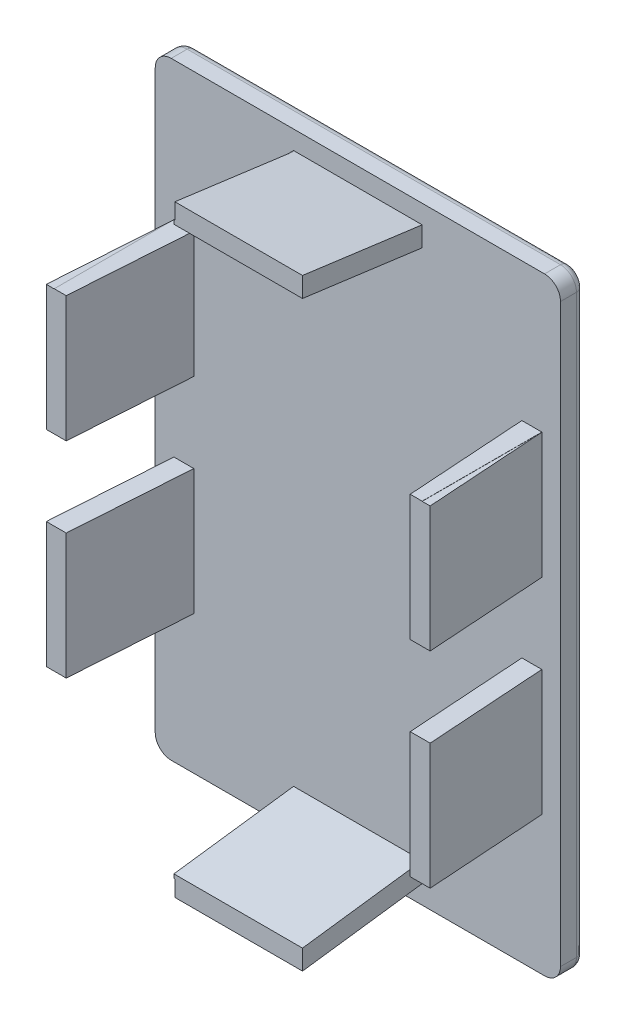
SolidWorks part; units mm, degrees
material "PLA"
ref_plane "Alzado" through (0, 0, 0) normal (0, 0, 1) x (1, 0, 0)
ref_plane "Planta" through (0, 0, 0) normal (0, 1, 0) x (1, 0, 0)
ref_plane "Vista lateral" through (0, 0, 0) normal (1, 0, 0) x (0, 0, -1)
sketch "Croquis1" plane through (0, 0, 0) normal (0, 0, 1) x (1, 0, 0)
  line L1 (25.4, 38.1) -> (-25.4, 38.1)
  line L2 (25.4, 38.1) -> (25.4, -38.1)
  line L3 (25.4, -38.1) -> (-25.4, -38.1)
  line L4 (-25.4, 38.1) -> (-25.4, -38.1)
  line L5 (25.4, 38.1) -> (-25.4, -38.1) construction
  line L6 (25.4, -38.1) -> (-25.4, 38.1) construction
  point P0 (0, 0)
  dimension "D1" = 76.2
  dimension "D2" = 50.8
extrude "Saliente-Extruir1" add sketch "Croquis1" along normal blind 18
sketch "Croquis2" plane through (0, 0, 18) normal (0, 0, 1) x (1, 0, 0)
  line L0 (25.4, 38.1) -> (-25.4, 38.1) construction
  line L1 (-23.06, 35.76) -> (23.06, 35.76)
  line L2 (-23.06, 35.76) -> (-23.06, -35.76)
  line L3 (-23.06, -35.76) -> (23.06, -35.76)
  line L4 (23.06, 35.76) -> (23.06, -35.76)
  line L5 (-25.4, -38.1) -> (25.4, -38.1) construction
  line L6 (-25.4, 38.1) -> (-25.4, -38.1) construction
  line L7 (25.4, -38.1) -> (25.4, 38.1) construction
  line L9 (-25.4, 38.1) -> (25.4, 38.1)
  line L10 (-25.4, 38.1) -> (-25.4, -38.1)
  line L11 (-25.4, -38.1) -> (25.4, -38.1)
  line L12 (25.4, 38.1) -> (25.4, -38.1)
  line L13 (-19.4, 32.1) -> (19.4, 32.1)
  line L14 (-19.4, 32.1) -> (-19.4, -32.1)
  line L15 (-19.4, -32.1) -> (19.4, -32.1)
  line L16 (19.4, 32.1) -> (19.4, -32.1)
  line M9 (-25.4, 38.1) -> (-25.4, -38.1)
  line M10 (-25.4, -38.1) -> (25.4, -38.1)
  line M11 (25.4, -38.1) -> (25.4, 38.1)
  line M12 (25.4, 38.1) -> (-25.4, 38.1)
  dimension "D1" = 2.34
  dimension "D2" = 2.34
  dimension "D3" = 2.34
  dimension "D4" = 2.34
  dimension "D5" = 6
  dimension "D6" = 6
  dimension "D7" = 6
  dimension "D8" = 6
extrude "Cortar-Extruir1" cut sketch "Croquis2" against normal blind 15 contours L1 L4 L3 L2 M12 M9 M10 M11 | L16 L13 L14 L15
sketch "Croquis3" plane through (0, 0, 18) normal (0, 0, 1) x (1, 0, 0)
  line L0 (-23.06, 35.76) -> (-23.06, -35.76) construction
  line L1 (-23.06, 22.1) -> (-19.4, 22.1)
  line L2 (-23.06, 22.1) -> (-23.06, -22.1)
  line L3 (-23.06, -22.1) -> (-19.4, -22.1)
  line L4 (-19.4, 22.1) -> (-19.4, -22.1)
  line L5 (-19.4, 32.1) -> (-19.4, -32.1) construction
  line L6 (-19.4, -32.1) -> (19.4, -32.1) construction
  line L7 (-9.4, -32.1) -> (9.3837, -32.1)
  line L8 (-9.4, -32.1) -> (-9.4, -35.76)
  line L9 (-9.4, -35.76) -> (9.3837, -35.76)
  line L10 (9.3837, -32.1) -> (9.3837, -35.76)
  line L11 (-23.06, -35.76) -> (23.06, -35.76) construction
  line L12 (19.4, 32.1) -> (19.4, -32.1) construction
  line L13 (19.4, -22.1) -> (23.06, -22.1)
  line L14 (19.4, -22.1) -> (19.4, 22.1)
  line L15 (19.4, 22.1) -> (23.06, 22.1)
  line L16 (23.06, -22.1) -> (23.06, 22.1)
  line L17 (23.06, 35.76) -> (23.06, -35.76) construction
  line L18 (-23.06, 35.76) -> (23.06, 35.76) construction
  line L19 (-9.4, 35.76) -> (9.4, 35.76)
  line L20 (-9.4, 35.76) -> (-9.4, 32.1)
  line L21 (-9.4, 32.1) -> (9.4, 32.1)
  line L22 (9.4, 35.76) -> (9.4, 32.1)
  line L23 (-19.4, 32.1) -> (19.4, 32.1) construction
  line L24 (-19.4, 32.1) -> (-19.4, -32.1) construction
  line L25 (19.4, 32.1) -> (19.4, -32.1) construction
  dimension "D1" = 10
  dimension "D2" = 10
  dimension "D3" = 10
  dimension "D4" = 10
  dimension "D5" = 10
  dimension "D6" = 10
  dimension "D7" = 10
extrude "Cortar-Extruir2" [suppressed] cut sketch "Croquis3" against normal blind 7
fillet "Redondeo1" [suppressed] radius 2
fillet "Redondeo2" [suppressed] radius 1
sketch "Croquis5" [suppressed] plane through (0, -38.1, 0) normal (0, -1, 0) x (1, 0, 0)
  line L0 (-23.4, 3) -> (23.4, 3) construction
  line L1 (-3, 3) -> (3, 3)
  line L2 (-3, 3) -> (-3, 1.5)
  line L3 (-3, 1.5) -> (3, 1.5)
  line L4 (3, 3) -> (3, 1.5)
  line L5 (0, 1) -> (0, 3) construction
  line L6 (-23.4, 1) -> (23.4, 1) construction
  dimension "D1" = 3
  dimension "D2" = 3
  dimension "D3" = 1.5
extrude "Cortar-Extruir4" [suppressed] cut sketch "Croquis5" against normal blind 6
sketch "Croquis6" plane through (0, 0, 18) normal (0, 0, 1) x (1, 0, 0)
  line L0 (-23.06, 35.76) -> (-8.06, 35.76)
  line L1 (-23.06, 35.76) -> (23.06, 35.76) construction
  line L2 (-8.06, 35.76) -> (-8.06, 32.1)
  line L3 (-19.4, 32.1) -> (19.4, 32.1) construction
  line L4 (-8.06, 32.1) -> (-19.4, 32.1)
  line L5 (-19.4, 32.1) -> (-19.4, 20.76)
  line L6 (-19.4, 32.1) -> (-19.4, -32.1) construction
  line L7 (-19.4, 20.76) -> (-23.06, 20.76)
  line L8 (-23.06, 35.76) -> (-23.06, -35.76) construction
  line L9 (-23.06, 20.76) -> (-23.06, 35.76)
  line L10 (23.06, 35.76) -> (8.06, 35.76)
  line L11 (-23.06, 35.76) -> (23.06, 35.76) construction
  line L12 (8.06, 35.76) -> (8.06, 32.1)
  line L13 (8.06, 32.1) -> (19.4, 32.1)
  line L14 (19.4, 32.1) -> (19.4, -32.1) construction
  line L15 (19.4, 32.1) -> (19.4, -32.1) construction
  line L16 (19.4, 32.1) -> (19.4, 20.76)
  line L17 (19.4, 20.76) -> (23.06, 20.76)
  line L18 (23.06, 35.76) -> (23.06, -35.76) construction
  line L19 (23.06, 20.76) -> (23.06, 35.76)
  line L20 (-23.06, -35.76) -> (-23.06, -20.76)
  line L21 (-23.06, 35.76) -> (-23.06, -35.76) construction
  line L22 (-23.06, -20.76) -> (-19.4, -20.76)
  line L23 (-19.4, 32.1) -> (-19.4, -32.1) construction
  line L24 (-19.4, -20.76) -> (-19.4, -32.1)
  line L25 (-19.4, -32.1) -> (-8.06, -32.1)
  line L26 (-19.4, -32.1) -> (19.4, -32.1) construction
  line L27 (-8.06, -32.1) -> (-8.06, -35.76)
  line L28 (-23.06, -35.76) -> (23.06, -35.76) construction
  line L29 (-8.06, -35.76) -> (-23.06, -35.76)
  line L30 (23.06, -35.76) -> (8.06, -35.76)
  line L31 (-23.06, -35.76) -> (23.06, -35.76) construction
  line L32 (8.06, -35.76) -> (8.06, -32.1)
  line L33 (-19.4, -32.1) -> (19.4, -32.1) construction
  line L34 (8.06, -32.1) -> (19.4, -32.1)
  line L35 (19.4, -32.1) -> (19.4, -20.76)
  line L36 (19.4, -20.76) -> (23.06, -20.76)
  line L37 (23.06, 35.76) -> (23.06, -35.76) construction
  line L38 (23.06, -20.76) -> (23.06, -35.76)
  dimension "D1" = 15
  dimension "D2" = 15
  dimension "D3" = 15
  dimension "D4" = 15
  dimension "D5" = 15
  dimension "D6" = 15
  dimension "D7" = 15
  dimension "D8" = 15
extrude "Cortar-Extruir8" cut sketch "Croquis6" against normal blind 15
sketch "Croquis10" plane through (0, -20.76, 0) normal (0, -1, 0) x (-1, 0, 0)
  line L0 (23.06, -18) -> (24.06, -18)
  line L1 (24.06, -18) -> (23.06, -3)
  line L2 (23.06, -3) -> (23.06, -18)
  line L3 (-23.06, -18) -> (-24.06, -18)
  line L4 (-24.06, -18) -> (-23.06, -3)
  line L5 (-23.06, -3) -> (-23.06, -18)
  dimension "D1" = 1
  dimension "D2" = 1
extrude "Saliente-Extruir3" add sketch "Croquis10" against normal blind 41.5
sketch "Croquis11" plane through (0, -20.76, 0) normal (0, -1, 0) x (1, 0, 0)
  line L0 (-19.4, 18) -> (-21.56, 18)
  line L1 (-19.4, 18) -> (-24.06, 18) construction
  line L2 (-21.56, 18) -> (-20.56, 3)
  line L3 (-19.4, 3) -> (-23.06, 3) construction
  line L4 (-20.56, 3) -> (-19.4, 3)
  line L5 (-19.4, 18) -> (-19.4, 3)
  dimension "D1" = 2.5
  dimension "D2" = 1.16
extrude "Cortar-Extruir9" cut sketch "Croquis11" against normal blind 51.5
sketch "Croquis12" plane through (0, -20.76, 0) normal (0, -1, 0) x (1, 0, 0)
  line L0 (19.4, 18) -> (19.4, 3)
  line L1 (19.4, 3) -> (20.56, 3)
  line L2 (23.06, 3) -> (19.4, 3) construction
  line L3 (20.56, 3) -> (21.56, 18)
  line L4 (24.06, 18) -> (19.4, 18) construction
  line L5 (21.56, 18) -> (19.4, 18)
  dimension "D1" = 2.5
  dimension "D2" = 1.16
extrude "Cortar-Extruir10" cut sketch "Croquis12" against normal blind 51.5
sketch "Croquis13" plane through (8.06, 0, 0) normal (1, 0, 0) x (0, 0, -1)
  line L0 (-18, -35.76) -> (-18, -37.76)
  line L1 (-18, -37.76) -> (-3, -35.76)
  line L2 (-3, -35.76) -> (-18, -35.76)
  line L3 (-18, 35.76) -> (-18, 37.76)
  line L4 (-18, 37.76) -> (-3, 35.76)
  line L5 (-3, 35.76) -> (-18, 35.76)
  dimension "D1" = 2
  dimension "D2" = 2
extrude "Saliente-Extruir4" add sketch "Croquis13" against normal blind 16
sketch "Croquis14" plane through (8.06, 0, 0) normal (1, 0, 0) x (0, 0, -1)
  line L0 (-3, -32.1) -> (-18, -32.1)
  line L1 (-18, -32.1) -> (-18, -35.26)
  line L2 (-18, -32.1) -> (-18, -37.76) construction
  line L3 (-18, -35.26) -> (-3, -33.26)
  line L4 (-3, -32.1) -> (-3, -35.76) construction
  line L5 (-3, -33.26) -> (-3, -32.1)
  line L6 (-18, 32.1) -> (-18, 35.26)
  line L7 (-18, 37.76) -> (-18, 32.1) construction
  line L8 (-18, 35.26) -> (-3, 33.26)
  line L9 (-3, 35.76) -> (-3, 32.1) construction
  line L10 (-3, 33.26) -> (-3, 32.1)
  line L11 (-3, 32.1) -> (-18, 32.1)
  dimension "D1" = 2.5
  dimension "D2" = 1.16
  dimension "D3" = 2.5
  dimension "D4" = 1.16
extrude "Cortar-Extruir11" cut sketch "Croquis14" against normal blind 16.5
fillet "Redondeo3" radius 2 4 edges at (25.4, 38.1, 1.5) (-25.4, 38.1, 1.5) (-25.4, -38.1, 1.5) (25.4, -38.1, 1.5)
fillet "Redondeo4" radius 1 8 edges at (-24.8142, 37.5142, 0) (-25.4, 0, 0) (-24.8142, -37.5142, 0) (0, -38.1, 0) (24.8142, -37.5142, 0) (25.4, 0, 0) (24.8142, 37.5142, 0) (0, 38.1, 0)
sketch "Croquis15" plane through (0, 0, 18) normal (0, 0, 1) x (1, 0, 0)
  line L0 (-24.06, -0.01) -> (24.06, -0.01) construction
  line L1 (-24.06, 20.74) -> (-24.06, -20.76) construction
  line L2 (24.06, 20.74) -> (24.06, -20.76) construction
  line L4 (-24.06, 4.99) -> (24.06, 4.99)
  line L5 (-24.06, 4.99) -> (-24.06, -5.01)
  line L6 (-24.06, -5.01) -> (24.06, -5.01)
  line L7 (24.06, 4.99) -> (24.06, -5.01)
  dimension "D1" = 5
  dimension "D2" = 5
extrude "Cortar-Extruir12" cut sketch "Croquis15" against normal blind 15
sketch "Croquis16" plane through (0, -38.1, 0) normal (0, -1, 0) x (1, 0, 0)
  line L0 (-23.4, 3) -> (23.4, 3) construction
  line L1 (-4, 3) -> (4, 3)
  line L2 (-4, 3) -> (-4, 1.5)
  line L3 (-4, 1.5) -> (4, 1.5)
  line L4 (4, 3) -> (4, 1.5)
  dimension "D1" = 1.5
  dimension "D2" = 8
  dimension "D3" = 4
extrude "Cortar-Extruir13" cut sketch "Croquis16" against normal blind 2
sketch "Croquis17" plane through (0, 0, 3) normal (0, 0, 1) x (1, 0, 0)
  line L1 (-23.4, -38.1) -> (-4, -38.1) construction
  line L2 (25.4, -36.1) -> (25.4, 36.1) construction
  circle A0 centre (13.4, -23.1) radius 3
  dimension "D3" = 6
  dimension "D1" = 12
  dimension "D2" = 15
extrude "Cortar-Extruir14" cut sketch "Croquis17" against normal blind 10
